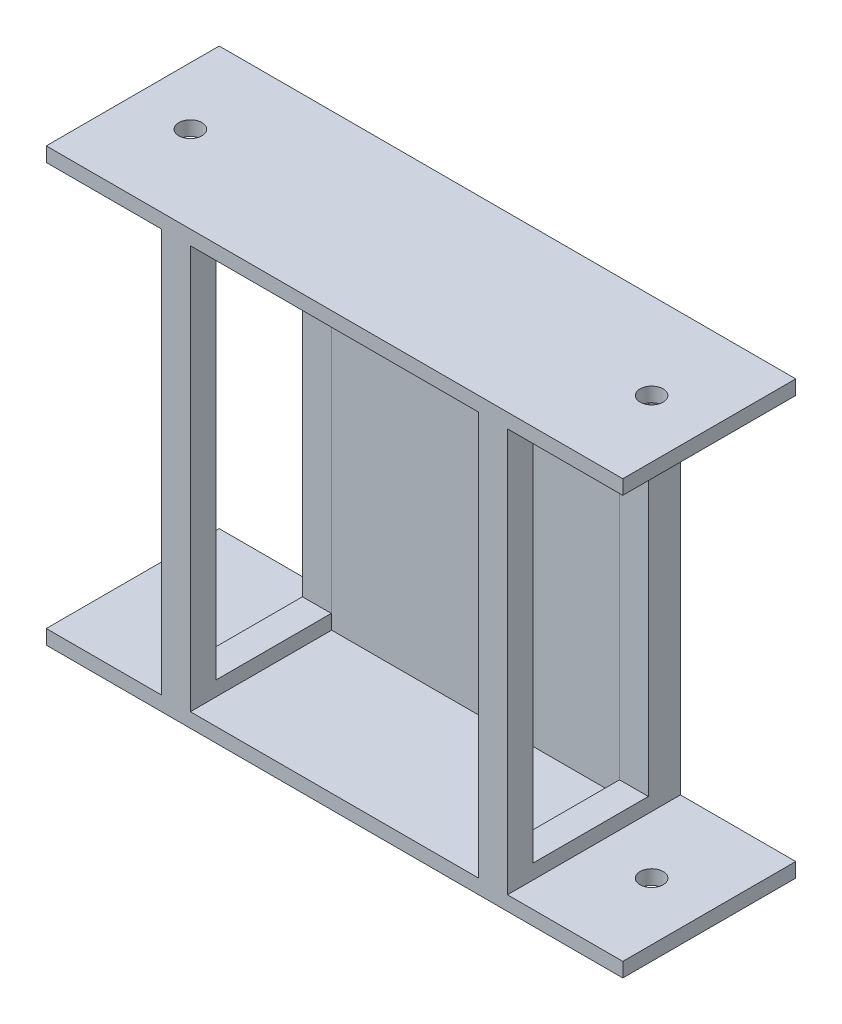
SolidWorks part; units mm, degrees
ref_plane "前视基准面" through (0, 0, 0) normal (0, 0, 1) x (1, 0, 0)
ref_plane "上视基准面" through (0, 0, 0) normal (0, 1, 0) x (1, 0, 0)
ref_plane "右视基准面" through (0, 0, 0) normal (1, 0, 0) x (0, 0, -1)
other "Configuration Table"
sketch "草图1" plane through (0, 0, 0) normal (0, 0, 1) x (1, 0, 0)
  line L0 (-100, 75) -> (100, 75)
  line L1 (-100, -75) -> (100, -75) construction
  line L2 (-100, -75) -> (-100, 75) construction
  line L3 (-100, 75) -> (100, 75) construction
  line L4 (100, -75) -> (100, 75) construction
  line L5 (-100, -75) -> (100, 75) construction
  line L6 (-100, 75) -> (100, -75) construction
  line L7 (-60, -75) -> (60, -75) construction
  line L8 (-60, -75) -> (-60, 75) construction
  line L9 (-60, 75) -> (60, 75) construction
  line L10 (60, -75) -> (60, 75) construction
  line L11 (-60, -75) -> (60, 75) construction
  line L12 (-60, 75) -> (60, -75) construction
  line L13 (-100, -70) -> (100, -70) construction
  line L14 (-100, -70) -> (-100, 70) construction
  line L15 (-100, 70) -> (100, 70) construction
  line L16 (100, -70) -> (100, 70) construction
  line L17 (-100, -70) -> (100, 70) construction
  line L18 (-100, 70) -> (100, -70) construction
  line L19 (100, 75) -> (100, 70)
  line L20 (100, 70) -> (60, 70)
  line L21 (60, 70) -> (60, -70)
  line L22 (60, -70) -> (100, -70)
  line L23 (100, -70) -> (100, -75)
  line L24 (100, -75) -> (-100, -75)
  line L25 (-100, -75) -> (-100, -70)
  line L26 (-100, -70) -> (-60, -70)
  line L27 (-60, -70) -> (-60, 70)
  line L28 (-60, 70) -> (-100, 70)
  line L29 (-100, 70) -> (-100, 75)
  point P0 (0, 0)
  point P6 (0, 0)
  point P11 (0, 0)
  dimension "D1" = 150
  dimension "D2" = 200
  dimension "D3" = 120
  dimension "D4" = 140
extrude "凸台-拉伸1" add sketch "草图1" along normal blind 60
sketch3d "3D草图1"
  point P0 (60, -3.1775, 32.5558)
ref_plane "基准面1" through (60, 0, 0) normal (1, 0, 0) x (0, 0, -1)
sketch "草图2" plane through (60, 0, 0) normal (1, 0, 0) x (0, 0, -1)
  line L0 (0, 82.5) -> (0, -82.5) construction
  line L1 (-60, 70) -> (0, 70) construction
  line L2 (-60, 70) -> (-60, -70) construction
  line L3 (-60, -70) -> (0, -70) construction
  line L4 (0, 70) -> (0, -70) construction
  line L5 (-60, -70) -> (0, -70) construction
  line L7 (-51.1304, -64.9012) -> (-11.1304, -64.9012)
  line L8 (-51.1304, -64.9012) -> (-51.1304, 65.0988)
  line L9 (-51.1304, 65.0988) -> (-11.1304, 65.0988)
  line L10 (-11.1304, -64.9012) -> (-11.1304, 65.0988)
  line L11 (-51.1304, -64.9012) -> (-11.1304, 65.0988) construction
  line L12 (-51.1304, 65.0988) -> (-11.1304, -64.9012) construction
  point P9 (-31.1304, 0.0988)
  dimension "D1" = 40
  dimension "D2" = 130
extrude "切除-拉伸1" cut sketch "草图2" against normal blind 136
sketch3d "3D草图2"
  point P0 (-14.2591, 19.067, 60)
ref_plane "基准面2" through (0, 0, 60) normal (0, 0, 1) x (1, 0, 0)
sketch "草图3" plane through (0, 0, 60) normal (0, 0, 1) x (1, 0, 0)
  line L0 (60, -50.9659) -> (60, 50.9659) construction
  line L1 (-60, 70) -> (60, 70) construction
  line L2 (-60, 70) -> (-60, -70) construction
  line L3 (-60, -70) -> (60, -70) construction
  line L4 (60, 70) -> (60, -70) construction
  line L6 (50, -70) -> (-50, -70)
  line L7 (50, -70) -> (50, 70)
  line L8 (50, 70) -> (-50, 70)
  line L9 (-50, -70) -> (-50, 70)
  line L10 (50, -70) -> (-50, 70) construction
  line L11 (50, 70) -> (-50, -70) construction
  point P7 (0, 0)
  dimension "D1" = 100
extrude "切除-拉伸2" cut sketch "草图3" against normal blind 49
sketch3d "3D草图3"
  point P0 (14.1533, -75, 27.0095)
ref_plane "基准面3" through (0, -75, 0) normal (0, -1, 0) x (1, 0, 0)
sketch "草图4" plane through (0, -75, 0) normal (0, -1, 0) x (1, 0, 0)
  line L0 (0, 60) -> (0, 0) construction
  line L1 (-100, 60) -> (100, 60) construction
  line L2 (-100, 60) -> (-100, 0) construction
  line L3 (-100, 0) -> (100, 0) construction
  line L4 (100, 60) -> (100, 0) construction
  line L5 (100, 30) -> (-100, 30) construction
  line L7 (-100, 30) -> (-80, 30) construction
  circle A0 centre (-80, 30) radius 4
  circle A1 centre (80, 30) radius 4
  point P12 (0, 30)
extrude "切除-拉伸3" cut sketch "草图4" against normal blind 198
